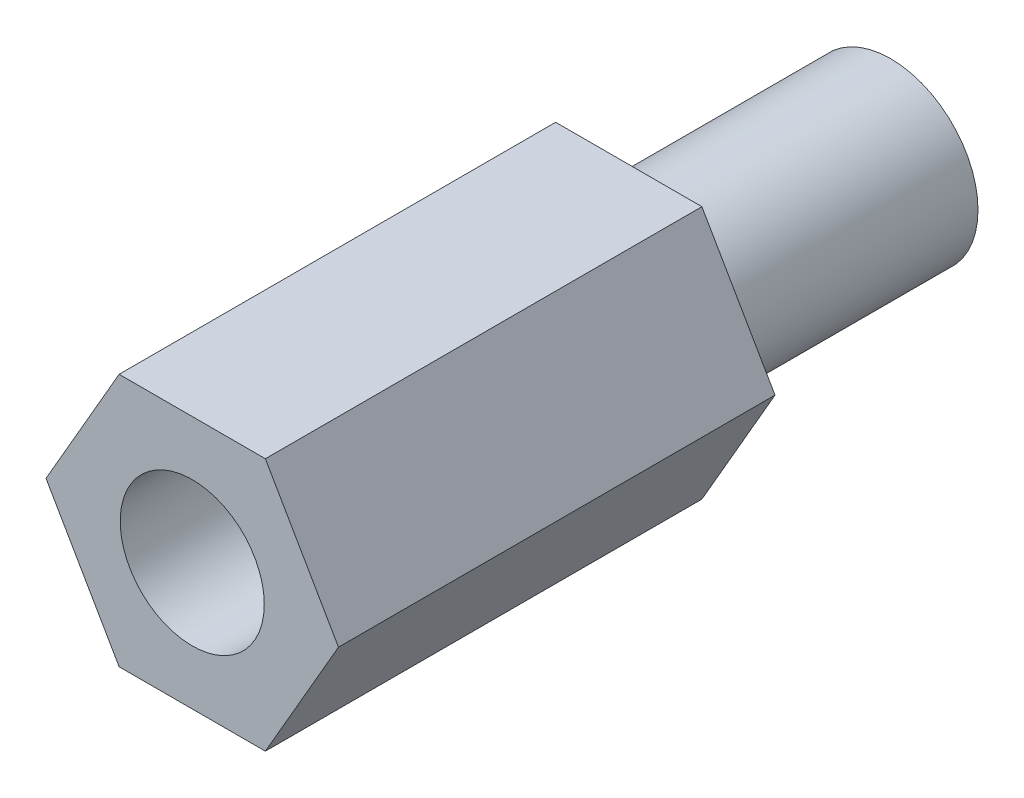
SolidWorks part; units mm, degrees
material "黃銅"
ref_plane "前基準面" through (0, 0, 0) normal (0, 0, 1) x (1, 0, 0)
ref_plane "上基準面" through (0, 0, 0) normal (0, 1, 0) x (1, 0, 0)
ref_plane "右基準面" through (0, 0, 0) normal (1, 0, 0) x (0, 0, -1)
sketch "草圖1" plane through (0, 0, 0) normal (0, 0, 1) x (1, 0, 0)
  line L1 (1.675, 2.9012) -> (-1.675, 2.9012)
  line L2 (-1.675, 2.9012) -> (-3.35, 0)
  line L3 (-3.35, 0) -> (-1.675, -2.9012)
  line L4 (-1.675, -2.9012) -> (1.675, -2.9012)
  line L5 (1.675, -2.9012) -> (3.35, 0)
  line L6 (3.35, 0) -> (1.675, 2.9012)
  circle A0 centre (0, 0) radius 2.9012 construction
  dimension "D1" = 6.7
extrude "填料-伸長1" add sketch "草圖1" along normal blind 10
sketch "草圖2" plane through (0, 0, 0) normal (0, 0, -1) x (-1, 0, 0)
  circle A0 centre (0, 0) radius 2
  dimension "D1" = 4
extrude "填料-伸長2" add sketch "草圖2" along normal blind 6
sketch "草圖3" plane through (0, 0, 10) normal (0, 0, 1) x (1, 0, 0)
  circle A0 centre (0, 0) radius 1.65
  dimension "D1" = 3.3
extrude "除料-伸長1" cut sketch "草圖3" against normal blind 5
